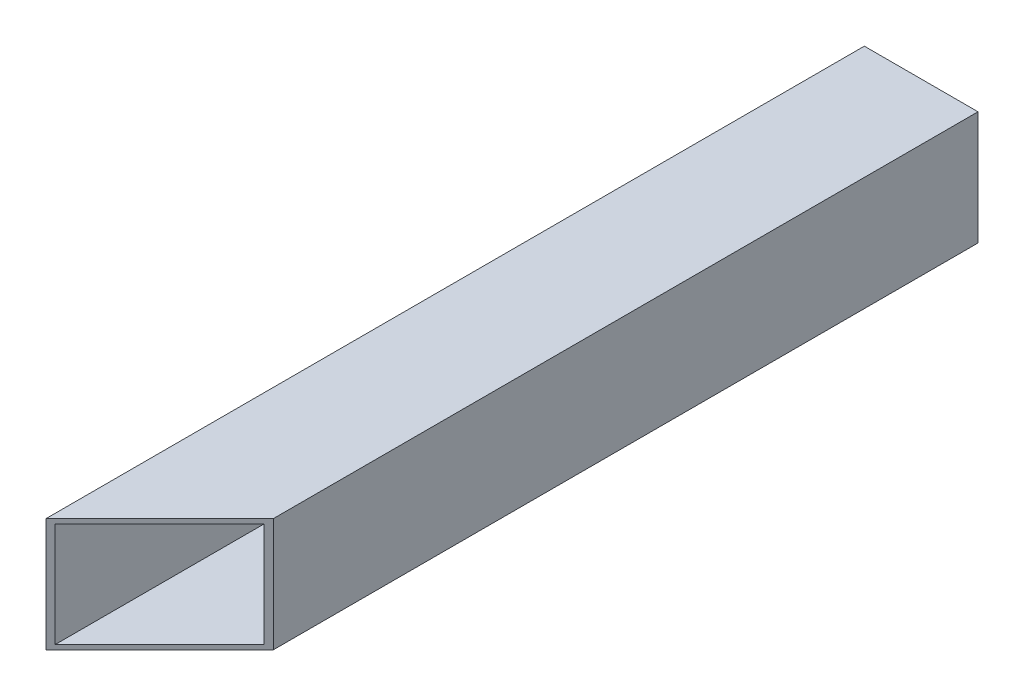
SolidWorks part; units mm, degrees
ref_plane "Front Plane" through (0, 0, 0) normal (0, 0, 1) x (1, 0, 0)
ref_plane "Top Plane" through (0, 0, 0) normal (0, 1, 0) x (1, 0, 0)
ref_plane "Right Plane" through (0, 0, 0) normal (1, 0, 0) x (0, 0, -1)
sketch "Sketch2" plane through (0, 0, 0) normal (0, 0, 1) x (1, 0, 0)
  line L1 (12.5, -12.5) -> (-12.5, -12.5)
  line L2 (12.5, -12.5) -> (12.5, 12.5)
  line L3 (12.5, 12.5) -> (-12.5, 12.5)
  line L4 (-12.5, -12.5) -> (-12.5, 12.5)
  line L5 (12.5, -12.5) -> (-12.5, 12.5) construction
  line L6 (12.5, 12.5) -> (-12.5, -12.5) construction
  line L7 (11.5, -11.5) -> (-11.5, -11.5)
  line L8 (11.5, -11.5) -> (11.5, 11.5)
  line L9 (11.5, 11.5) -> (-11.5, 11.5)
  line L10 (-11.5, -11.5) -> (-11.5, 11.5)
  line L11 (11.5, -11.5) -> (-11.5, 11.5) construction
  line L12 (11.5, 11.5) -> (-11.5, -11.5) construction
  point P0 (0, 0)
  point P6 (0, 0)
  dimension "D1" = 25
  dimension "D2" = 1
extrude "Boss-Extrude1" add sketch "Sketch2" along normal blind 180
sketch "Sketch3" plane through (0, 12.5, 0) normal (0, 1, 0) x (1, 0, 0)
  line L4 (12.5, -180) -> (12.5, -155)
  line L5 (12.5, -180) -> (12.5, 0) construction
  line L6 (12.5, -155) -> (-12.5, -180)
  line L7 (12.5, -180) -> (-12.5, -180) construction
  line L8 (-12.5, -180) -> (-12.5, 0) construction
  line L9 (-12.5, -180) -> (12.5, -180)
  dimension "D1" = 45
extrude "Cut-Extrude1" cut sketch "Sketch3" against normal blind 210
